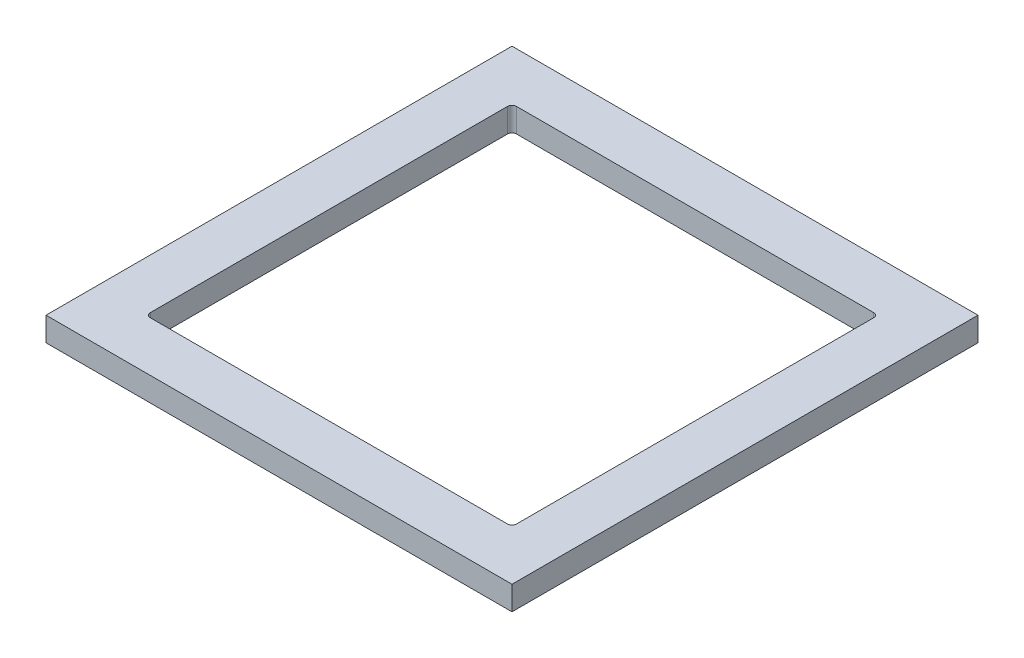
SolidWorks part; units mm, degrees
material "Pine"
ref_plane "Front Plane" through (0, 0, 0) normal (0, 0, 1) x (1, 0, 0)
ref_plane "Top Plane" through (0, 0, 0) normal (0, 1, 0) x (1, 0, 0)
ref_plane "Right Plane" through (0, 0, 0) normal (1, 0, 0) x (0, 0, -1)
sketch "Sketch1" plane through (0, 0, 0) normal (0, 1, 0) x (1, 0, 0)
  line L1 (-177.8, 177.8) -> (177.8, 177.8)
  line L2 (-177.8, 177.8) -> (-177.8, -177.8)
  line L3 (-177.8, -177.8) -> (177.8, -177.8)
  line L4 (177.8, 177.8) -> (177.8, -177.8)
  line L5 (0, -177.8) -> (0, 177.8) construction
  line L6 (-177.8, 0) -> (177.8, 0) construction
  point P0 (0, 0)
  dimension "D1" = 355.6
extrude "Boss-Extrude1" add sketch "Sketch1" along normal blind 18.2562
sketch "Sketch3" plane through (0, 18.2562, 0) normal (0, 1, 0) x (1, 0, 0)
  line L0 (0, -142.875) -> (0, 142.875) construction
  line L1 (-142.875, 0) -> (142.875, 0) construction
  point P4 (0, 0)
  point P8 (0, 0)
  dimension "D1" = 285.75
sketch "Sketch8" plane through (0, 18.2562, 0) normal (0, 1, 0) x (1, 0, 0)
  line L0 (-177.8, 177.8) -> (-177.8, -177.8) construction
  line L1 (139.7, 139.7) -> (-139.7, 139.7)
  line L2 (139.7, 139.7) -> (139.7, -139.7)
  line L3 (139.7, -139.7) -> (-139.7, -139.7)
  line L4 (-139.7, 139.7) -> (-139.7, -139.7)
  line L5 (139.7, 139.7) -> (-139.7, -139.7) construction
  line L6 (139.7, -139.7) -> (-139.7, 139.7) construction
  point P0 (0, 0)
  dimension "D1" = 38.1
extrude "Cut-Extrude3" cut sketch "Sketch8" against normal through all
fillet "Fillet2" radius 3.3782 4 edges at (139.7, 9.1281, -139.7) (139.7, 9.1281, 139.7) (-139.7, 9.1281, -139.7) (-139.7, 9.1281, 139.7)
